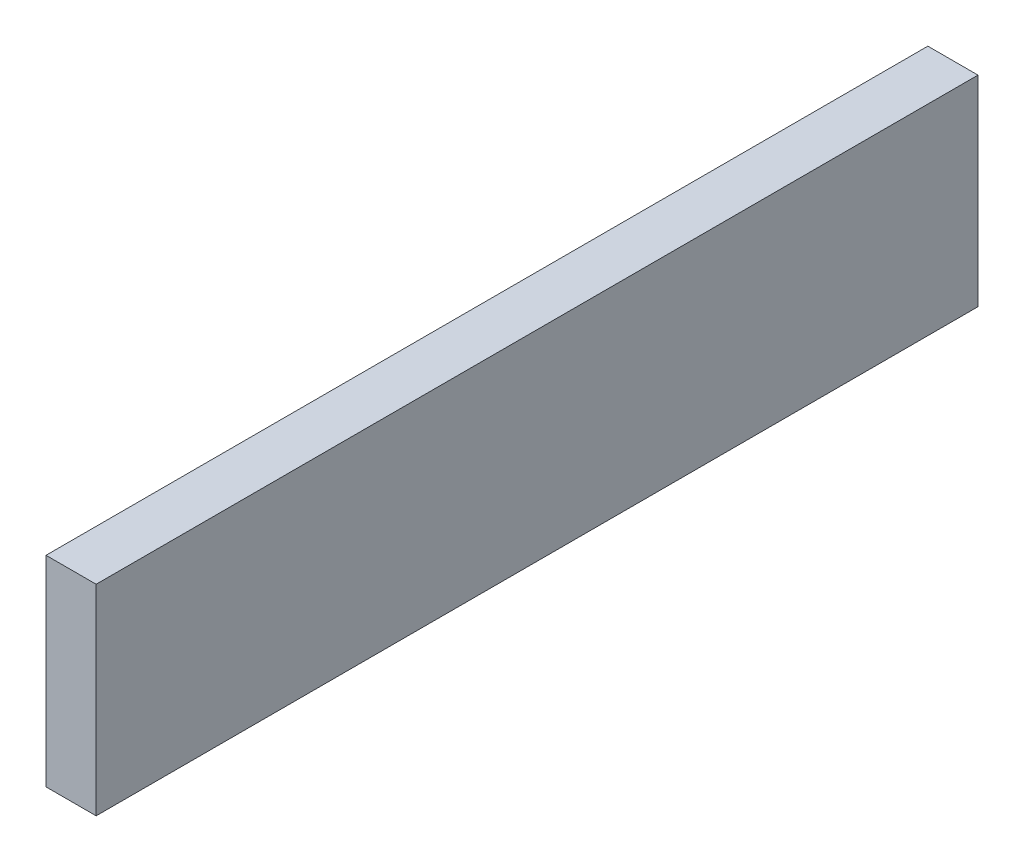
SolidWorks part; units mm, degrees
material "Low Carbon Steel"
ref_plane "Front Plane" through (0, 0, 0) normal (0, 0, 1) x (1, 0, 0)
ref_plane "Top Plane" through (0, 0, 0) normal (0, 1, 0) x (1, 0, 0)
ref_plane "Right Plane" through (0, 0, 0) normal (1, 0, 0) x (0, 0, -1)
sketch "Sketch1" plane through (0, 0, 0) normal (1, 0, 0) x (0, 0, -1)
  line L0 (-335, -76.2) -> (335, 76.2) construction
  line L1 (-335, 76.2) -> (335, 76.2)
  line L2 (-335, 76.2) -> (-335, -76.2)
  line L3 (-335, -76.2) -> (335, -76.2)
  line L4 (335, 76.2) -> (335, -76.2)
  dimension "D1" = 670
  dimension "D2" = 152.4
extrude "Boss-Extrude1" add sketch "Sketch1" along normal blind 38.1
other "Freeze***"
